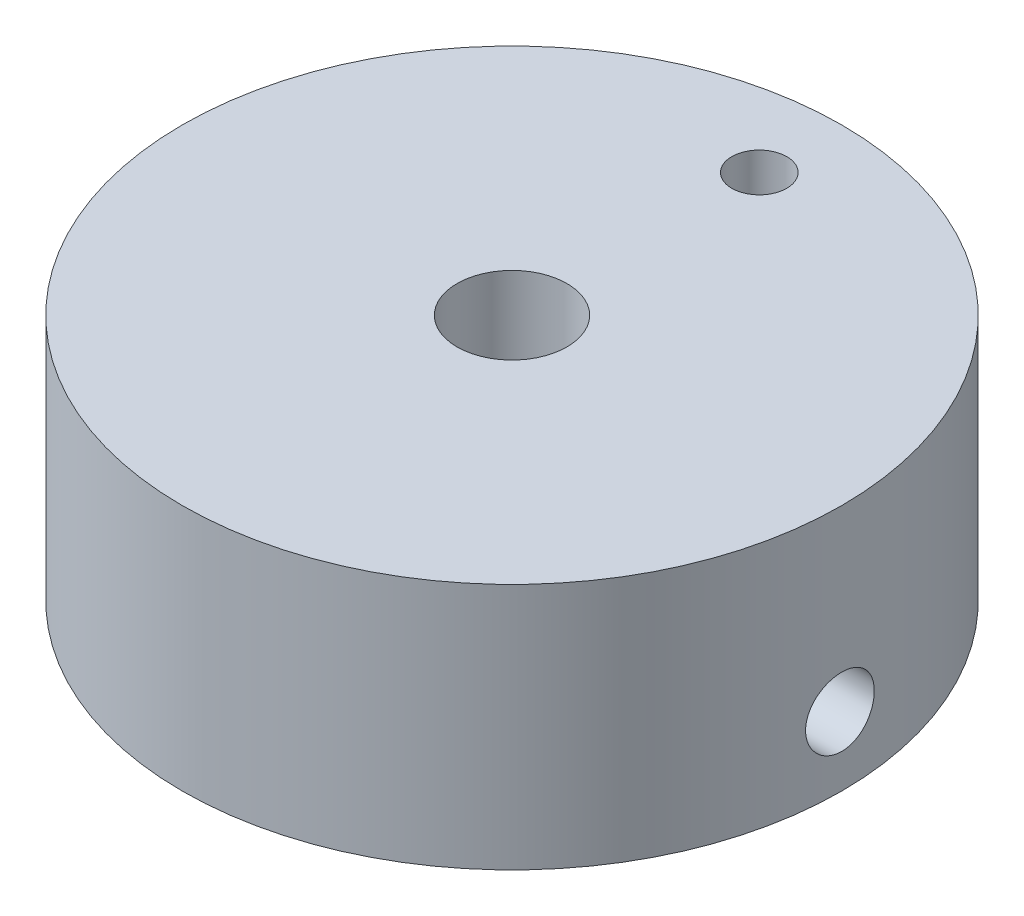
SolidWorks part; units mm, degrees
ref_plane "前视基准面" through (0, 0, 0) normal (0, 0, 1) x (1, 0, 0)
ref_plane "上视基准面" through (0, 0, 0) normal (0, 1, 0) x (1, 0, 0)
ref_plane "右视基准面" through (0, 0, 0) normal (1, 0, 0) x (0, 0, -1)
sketch "草图1" plane through (0, 0, 0) normal (0, 1, 0) x (1, 0, 0)
  circle A0 centre (0, 0) radius 12
  dimension "D1" = 24
extrude "凸台-拉伸1" add sketch "草图1" along normal blind 9
sketch "草图2" plane through (0, 9, 0) normal (0, 1, 0) x (1, 0, 0)
  circle A0 centre (0, 0) radius 2
  dimension "D1" = 4
extrude "切除-拉伸1" cut sketch "草图2" against normal through all
sketch "草图3" plane through (0, 9, 0) normal (0, 1, 0) x (1, 0, 0)
  circle A0 centre (0, 9) radius 1
  dimension "D1" = 2
  dimension "D2" = 9
extrude "切除-拉伸2" cut sketch "草图3" against normal blind 3
sketch "草图4" plane through (0, 0, 0) normal (1, 0, 0) x (0, 0, -1)
  circle A0 centre (0, 2.5) radius 1.25
  dimension "D1" = 2.5
  dimension "D2" = 2.5
extrude "切除-拉伸3" cut sketch "草图4" along normal blind 13
cosmetic thread "装饰螺纹线1"
sketch "草图5" plane through (0, 0, 0) normal (0, -1, 0) x (1, 0, 0)
  circle A0 centre (0, 0) radius 3.5
  circle A1 centre (0, 0) radius 7.5
  dimension "D1" = 7
  dimension "D2" = 15
extrude "切除-拉伸4" cut sketch "草图5" against normal blind 0.3
sketch "草图6" plane through (0, 0, 0) normal (0, 0, 1) x (1, 0, 0)
  line L0 (0, 0) -> (0, 12.6242) construction
  line L1 (12, 7.8274) -> (11, 7.25)
  line L2 (11, 7.25) -> (11, 6.75)
  line L3 (11, 6.75) -> (12, 6.1726)
  line L4 (12, 3.75) -> (12, 9) construction
  line L5 (12, 6.1726) -> (12, 7.8274)
  line L6 (0, 7) -> (10.6888, 7) construction
  line L7 (12, 9) -> (-12, 9) construction
  dimension "D1" = 60
  dimension "D2" = 1
  dimension "D3" = 2
  dimension "D4" = 0.5
